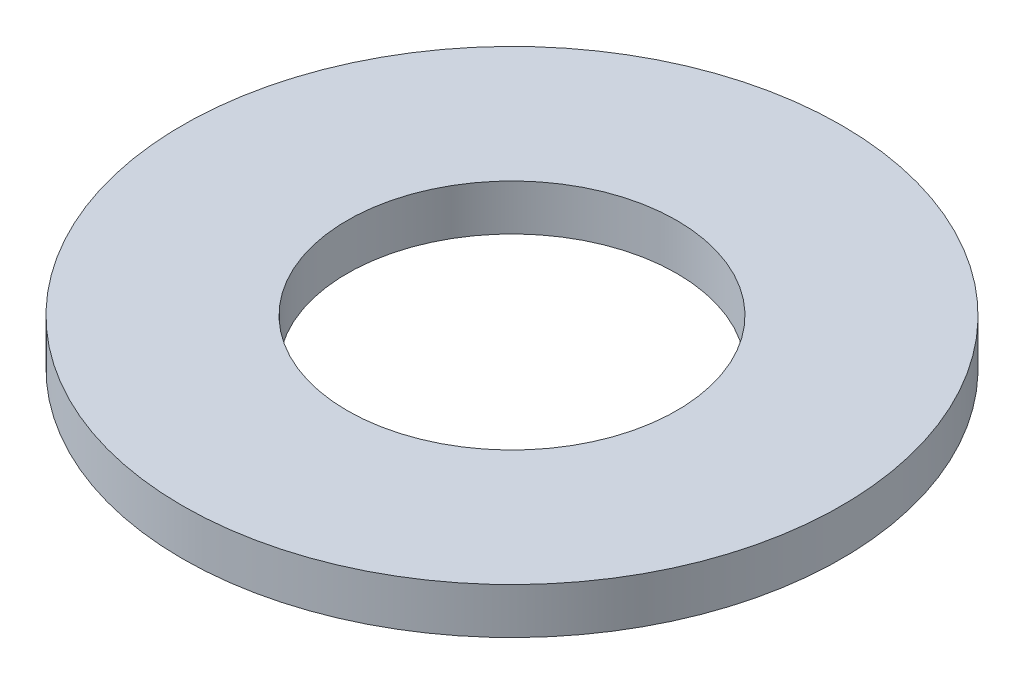
SolidWorks part; units mm, degrees
ref_plane "Front Plane" through (0, 0, 0) normal (0, 0, 1) x (1, 0, 0)
ref_plane "Top Plane" through (0, 0, 0) normal (0, 1, 0) x (1, 0, 0)
ref_plane "Right Plane" through (0, 0, 0) normal (1, 0, 0) x (0, 0, -1)
sketch "Sketch1" plane through (0, 0, 0) normal (0, 1, 0) x (1, 0, 0)
  circle A0 centre (0, 0) radius 13.4938
  circle A1 centre (0, 0) radius 6.7469
  dimension "D1" = 26.9875
  dimension "D2" = 13.4937
extrude "Boss-Extrude1" add sketch "Sketch1" along normal blind 1.8796
